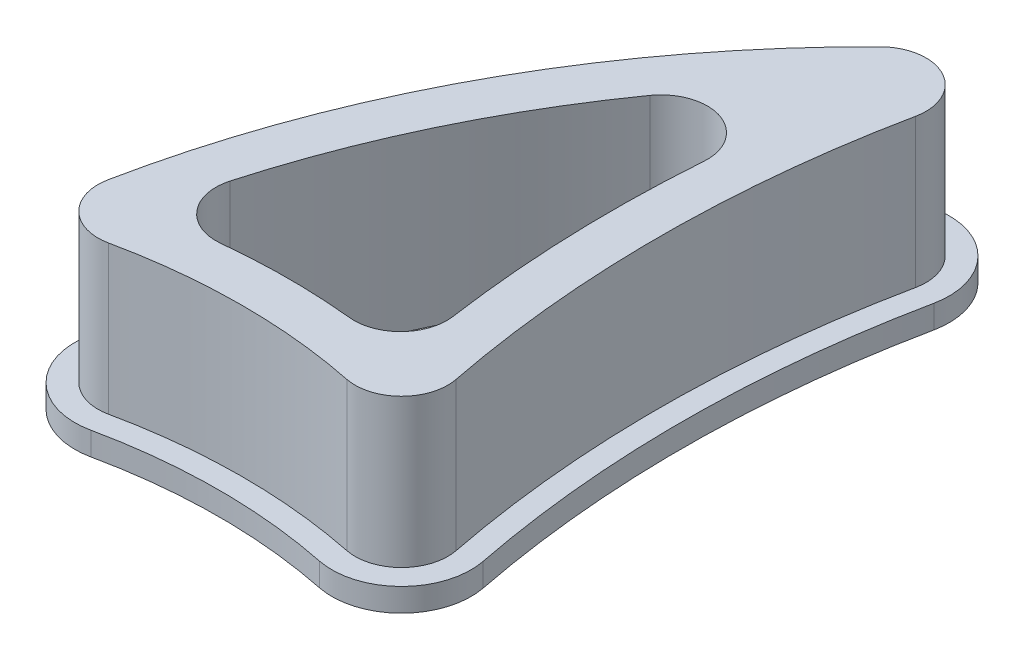
SolidWorks part; units mm, degrees
ref_plane "前视基准面" through (0, 0, 0) normal (0, 0, 1) x (1, 0, 0)
ref_plane "上视基准面" through (0, 0, 0) normal (0, 1, 0) x (1, 0, 0)
ref_plane "右视基准面" through (0, 0, 0) normal (1, 0, 0) x (0, 0, -1)
other "Configuration Table"
sketch "草图1" plane through (0, 0, 0) normal (0, 1, 0) x (1, 0, 0)
  arc A0 (9.4083, -18.959) -> (9.4891, 0.8001) centre (58.4625, -9.2799) cw
  arc A1 (6.126, 2.6274) -> (-5.5617, -19.0002) centre (35.6141, -27.2799) ccw
  arc A2 (-3.1832, -21.3503) -> (7.0456, -21.3057) centre (2.038, -45.799) cw
  arc A3 (-5.5617, -19.0002) -> (-3.1832, -21.3503) centre (-3.6009, -19.3944) ccw
  arc A4 (7.0456, -21.3057) -> (9.4083, -18.959) centre (7.4462, -19.3462) ccw
  arc A5 (6.126, 2.6274) -> (9.4891, 0.8001) centre (7.5302, 1.2033) cw
  arc A6 (2.9768, -4.1542) -> (-2.8808, -16.4105) centre (35.6141, -27.2799) ccw
  arc A7 (-0.7495, -18.9433) -> (4.8053, -18.9412) centre (2.038, -45.799) cw
  arc A8 (6.99, -16.6676) -> (6.6032, -5.4575) centre (58.4625, -9.2799) cw
  arc A9 (-2.8808, -16.4105) -> (-0.7495, -18.9433) centre (-0.956, -16.954) ccw
  arc A10 (4.8053, -18.9412) -> (6.99, -16.6676) centre (5.0103, -16.9517) ccw
  arc A11 (6.6032, -5.4575) -> (2.9768, -4.1542) centre (4.6086, -5.3104) ccw
  dimension "D1" = 2
extrude "凸台-拉伸1" add sketch "草图1" along normal blind 6.4
sketch "草图2" plane through (0, 0, 0) normal (0, -1, 0) x (1, 0, 0)
  arc A28 (5.4239, -3.3395) -> (10.4686, -0.5985) centre (7.5302, -1.2033) ccw
  arc A29 (-6.542, 18.803) -> (5.4239, -3.3395) centre (35.6141, 27.2799) ccw
  arc A30 (-2.9744, 22.3283) -> (-6.542, 18.803) centre (-3.6009, 19.3944) ccw
  arc A31 (-2.9744, 22.3283) -> (6.8452, 22.2854) centre (2.038, 45.799) ccw
  arc A32 (10.3894, 18.7655) -> (6.8452, 22.2854) centre (7.4462, 19.3462) ccw
  arc A33 (10.3894, 18.7655) -> (10.4686, -0.5985) centre (58.4625, 9.2799) ccw
  arc A34 (5.4239, -3.3395) -> (10.4686, -0.5985) centre (7.5302, -1.2033) ccw
  arc A35 (-6.542, 18.803) -> (5.4239, -3.3395) centre (35.6141, 27.2799) ccw
  arc A36 (-2.9744, 22.3283) -> (-6.542, 18.803) centre (-3.6009, 19.3944) ccw
  arc A37 (-2.9744, 22.3283) -> (6.8452, 22.2854) centre (2.038, 45.799) ccw
  arc A38 (10.3894, 18.7655) -> (6.8452, 22.2854) centre (7.4462, 19.3462) ccw
  arc A39 (10.3894, 18.7655) -> (10.4686, -0.5985) centre (58.4625, 9.2799) ccw
  arc A61 (2.9768, 4.1542) -> (6.6032, 5.4575) centre (4.6086, 5.3104) ccw
  arc A62 (6.99, 16.6676) -> (6.6032, 5.4575) centre (58.4625, 9.2799) ccw
  arc A63 (6.99, 16.6676) -> (4.8053, 18.9412) centre (5.0103, 16.9517) ccw
  arc A64 (-0.7495, 18.9433) -> (4.8053, 18.9412) centre (2.038, 45.799) ccw
  arc A65 (-2.8808, 16.4105) -> (2.9768, 4.1542) centre (35.6141, 27.2799) ccw
  arc A66 (-0.7495, 18.9433) -> (-2.8808, 16.4105) centre (-0.956, 16.954) ccw
  arc A67 (2.9768, 4.1542) -> (6.6032, 5.4575) centre (4.6086, 5.3104) ccw
  arc A68 (6.99, 16.6676) -> (6.6032, 5.4575) centre (58.4625, 9.2799) ccw
  arc A69 (6.99, 16.6676) -> (4.8053, 18.9412) centre (5.0103, 16.9517) ccw
  arc A70 (-0.7495, 18.9433) -> (4.8053, 18.9412) centre (2.038, 45.799) ccw
  arc A71 (-2.8808, 16.4105) -> (2.9768, 4.1542) centre (35.6141, 27.2799) ccw
  arc A72 (-0.7495, 18.9433) -> (-2.8808, 16.4105) centre (-0.956, 16.954) ccw
  dimension "D1" = 1
  dimension "D2" = 0
extrude "凸台-拉伸2" add sketch "草图2" along normal blind 1
